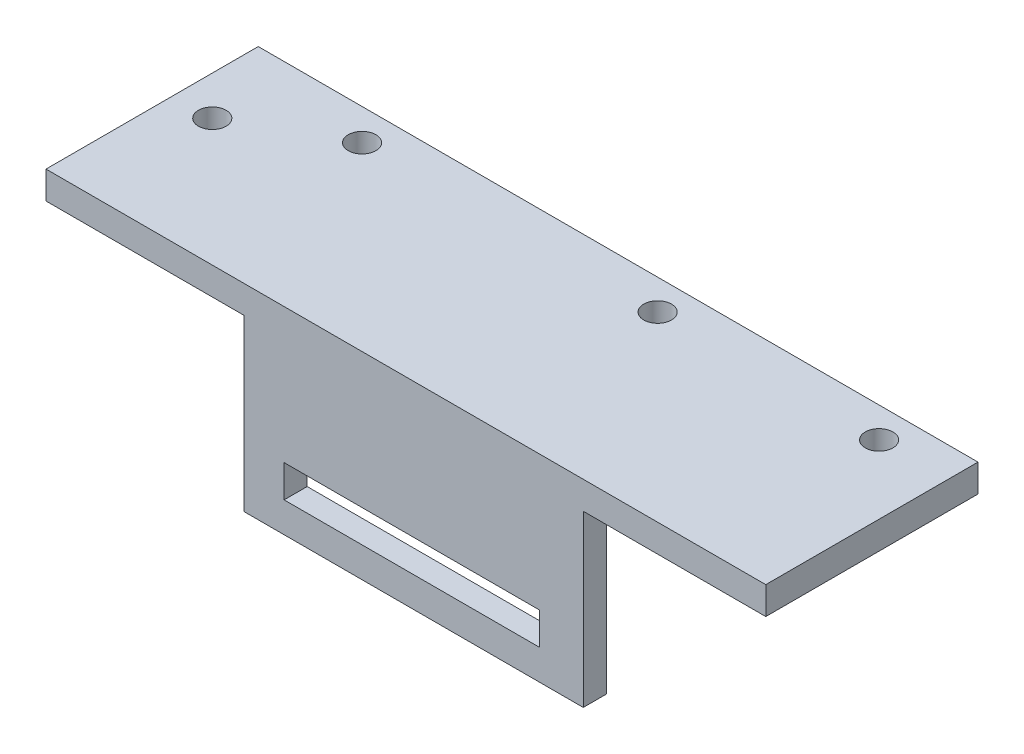
SolidWorks part; units mm, degrees
ref_plane "前视基准面" through (0, 0, 0) normal (0, 0, 1) x (1, 0, 0)
ref_plane "上视基准面" through (0, 0, 0) normal (0, 1, 0) x (1, 0, 0)
ref_plane "右视基准面" through (0, 0, 0) normal (1, 0, 0) x (0, 0, -1)
other "Configuration Table"
sketch "草图1" plane through (0, 0, 0) normal (0, 1, 0) x (1, 0, 0)
  line L1 (-39, -7.5) -> (39, -7.5)
  line L2 (-39, -7.5) -> (-39, 7.5)
  line L3 (-39, 7.5) -> (39, 7.5)
  line L4 (39, -7.5) -> (39, 7.5)
  line L5 (-39, -7.5) -> (39, 7.5) construction
  line L6 (-39, 7.5) -> (39, -7.5) construction
  point P0 (0, 0)
  dimension "D1" = 15
  dimension "D2" = 78
extrude "凸台-拉伸1" add sketch "草图1" along normal blind 3 contours L2 L1 L4 L3
sketch "草图3" plane through (0, 3, 0) normal (0, 1, 0) x (1, 0, 0)
  line L0 (-39, -7.5) -> (-39, 7.5) construction
  line L1 (-39, 7.5) -> (39, 7.5) construction
  circle A0 centre (-34.76, -1.72) radius 1.5
  circle A1 centre (-24.35, 4.1) radius 1.5
  circle A2 centre (31.56, 4.2217) radius 1.5
  circle A3 centre (7.56, 4.2217) radius 1.5
  point P2 (0, 0)
  point P11 (27.5737, 4.2217)
  point P12 (6.7297, 4.2217)
  point P13 (-31.0334, 4.2217)
  point P14 (-26.0415, 4.2217)
  point P17 (-24.5173, 0.3349)
  dimension "D1" = 4.24
  dimension "D2" = 10.41
  dimension "D3" = 3.4
  dimension "D4" = 5.82
  dimension "D5" = 31.91
  dimension "D6" = 24
extrude "切除-拉伸1" cut sketch "草图3" against normal blind 3
sketch "草图4" plane through (0, 3, 0) normal (0, 1, 0) x (1, 0, 0)
  line L0 (-39, -7.5) -> (-39, 7.5) construction
  circle A0 centre (-3, -1.2342) radius 6
  point P4 (-3, -1.2342)
  dimension "D1" = 36
extrude "凸台-拉伸2" add sketch "草图4" along normal blind 18
sketch "草图5" plane through (0, 21, 0) normal (0, 1, 0) x (1, 0, 0)
  circle A0 centre (-3, -1.2342) radius 4.5
extrude "切除-拉伸2" cut sketch "草图5" against normal blind 21
hole_wizard "Ø2.0mm 暗销孔2" positions "3D草图5" profile "草图8" hole size "Ø2.0" standard "ANSI Metric"
sketch3d "3D草图5"
  point P0 (-7.9013, 17.3421, 4.6949)
  point P2 (1.0718, 17.1648, 5.6411)
sketch "草图8" plane through (-7.9013, 17.3421, 4.6949) normal (0, 1, 0) x (0.5768, 0, 0.8169)
  line L0 (0, 0) -> (0, 6)
  line L1 (0, 6) -> (1.5, 4.5)
  line L2 (1.5, 4.5) -> (1.5, 0)
  line L5 (1.5, 0) -> (0, 0)
  line L10 (0, 6) -> (-1.5, 4.5) construction
  line L11 (0, -6.35) -> (0, 107.95) construction
  dimension "孔直径" = 3
  dimension "孔深度" = 6
  dimension "导头角度" = 90
sketch "草图10" plane through (0, 0, -7.5) normal (0, 0, -1) x (-1, 0, 0)
  line L0 (39, 3) -> (-39, 3) construction
  line L1 (0, 3) -> (6, 3)
  line L2 (0, 3) -> (0, 13)
  line L3 (0, 13) -> (6, 13)
  line L4 (6, 3) -> (6, 13)
  point P6 (6.8148, 13.7899)
  point P7 (6.7809, 13.0053)
  point P8 (0, 0)
  point P9 (7.0332, 12.5658)
  dimension "D1" = 6
  dimension "D2" = 10
extrude "切除-拉伸3" cut sketch "草图10" against normal blind 7
sketch "草图13" plane through (0, 0, -7.5) normal (0, 0, -1) x (-1, 0, 0)
  line L0 (39, 3) -> (-39, 3) construction
  line L1 (-6.6034, 3) -> (13.2323, 3)
  line L2 (-6.6034, 3) -> (-6.6034, 24.6102)
  line L3 (-6.6034, 24.6102) -> (13.2323, 24.6102)
  line L4 (13.2323, 3) -> (13.2323, 24.6102)
extrude "切除-拉伸4" cut sketch "草图13" against normal blind 20
sketch "草图14" plane through (0, 3, 0) normal (0, 1, 0) x (1, 0, 0)
  line L1 (-8.751, 3.9817) -> (2.7721, 3.9817)
  line L2 (-8.751, 3.9817) -> (-8.751, -6.5086)
  line L3 (-8.751, -6.5086) -> (2.7721, -6.5086)
  line L4 (2.7721, 3.9817) -> (2.7721, -6.5086)
extrude "凸台-拉伸3" add sketch "草图14" against normal blind 3
sketch "草图18" plane through (0, 0, 0) normal (0, -1, 0) x (1, 0, 0)
  line L1 (-39, 7.5) -> (39, 7.5)
  line L2 (-39, 7.5) -> (-39, 15.5)
  line L3 (-39, 15.5) -> (39, 15.5)
  line L4 (39, 7.5) -> (39, 15.5)
  dimension "D1" = 8
extrude "凸台-拉伸4" add sketch "草图18" against normal blind 3
sketch "草图19" plane through (0, 0, 0) normal (0, -1, 0) x (1, 0, 0)
  line L0 (39, 15.5) -> (-39, 15.5) construction
  line L1 (-17.5447, 15.5) -> (19.2232, 15.5)
  line L2 (-17.5447, 15.5) -> (-17.5447, 13)
  line L3 (-17.5447, 13) -> (19.2232, 13)
  line L4 (19.2232, 15.5) -> (19.2232, 13)
  dimension "D1" = 2.5
extrude "凸台-拉伸5" add sketch "草图19" along normal blind 12.5
sketch "草图20" plane through (0, 0, 13) normal (0, 0, -1) x (-1, 0, 0)
  circle A0 centre (-6.7687, -6.2144) radius 1.65
  circle A1 centre (6.2313, -6.2144) radius 1.65
  point P4 (0, 0)
  point P5 (0, 0)
  point P6 (1.0873, -6.2144)
  dimension "D1" = 13
sketch "草图23" plane through (0, 0, 13) normal (0, 0, -1) x (-1, 0, 0)
  line L0 (-19.2232, -12.5) -> (-19.2232, 0) construction
  circle A4 centre (-8.6032, -6.0559) radius 1.65
  circle A5 centre (2.5968, -6.0559) radius 1.65
  dimension "D1" = 10.62
  dimension "D2" = 11.2
extrude "切除-拉伸6" cut sketch "草图23" against normal blind 12.5
sketch "草图24" plane through (0, 0, 13) normal (0, 0, -1) x (-1, 0, 0)
  circle A0 centre (-8.6032, -6.0559) radius 1.65 construction
  circle A1 centre (-8.6032, -6.0559) radius 1.65
  circle A2 centre (2.5968, -6.0559) radius 1.65 construction
  circle A3 centre (2.5968, -6.0559) radius 1.65
  circle A4 centre (4.1968, -6.0559) radius 1.6
  dimension "D2" = 12.8
  dimension "D1" = 11.2
sketch "草图25" plane through (0, 0, 13) normal (0, 0, -1) x (-1, 0, 0)
  line L1 (0.2124, -3.7444) -> (4.449, -3.7444)
  line L2 (0.2124, -3.7444) -> (0.2124, -9.1085)
  line L3 (0.2124, -9.1085) -> (4.449, -9.1085)
  line L4 (4.449, -3.7444) -> (4.449, -9.1085)
extrude "凸台-拉伸7" add sketch "草图25" against normal blind 2.5
sketch "草图26" plane through (0, 0, 13) normal (0, 0, -1) x (-1, 0, 0)
  circle A0 centre (4.1968, -6.0559) radius 1.6 construction
  circle A1 centre (4.1968, -6.0559) radius 1.6
extrude "切除-拉伸7" cut sketch "草图26" against normal blind 2.5
sketch "草图27" plane through (0, 0, 13) normal (0, 0, -1) x (-1, 0, 0)
  line L1 (-13.0523, -3.3946) -> (8.2937, -3.3946)
  line L2 (-13.0523, -3.3946) -> (-13.0523, -9.9889)
  line L3 (-13.0523, -9.9889) -> (8.2937, -9.9889)
  line L4 (8.2937, -3.3946) -> (8.2937, -9.9889)
extrude "凸台-拉伸8" add sketch "草图27" against normal blind 2.5
sketch "草图28" plane through (0, 0, 13) normal (0, 0, -1) x (-1, 0, 0)
  line L1 (-19.2232, -12.5) -> (17.544, -12.5)
  line L2 (-19.2232, -12.5) -> (-19.2232, -18.4182)
  line L3 (-19.2232, -18.4182) -> (17.544, -18.4182)
  line L4 (17.544, -12.5) -> (17.544, -18.4182)
extrude "凸台-拉伸9" add sketch "草图28" against normal blind 2.5
sketch "草图29" plane through (0, 0, 13) normal (0, 0, -1) x (-1, 0, 0)
  line L1 (-14.4639, -11.6442) -> (13.1964, -11.6442)
  line L2 (-14.4639, -11.6442) -> (-14.4639, -15.1442)
  line L3 (-14.4639, -15.1442) -> (13.1964, -15.1442)
  line L4 (13.1964, -11.6442) -> (13.1964, -15.1442)
  dimension "D1" = 3.5
extrude "切除-拉伸9" cut sketch "草图29" against normal blind 2.5
